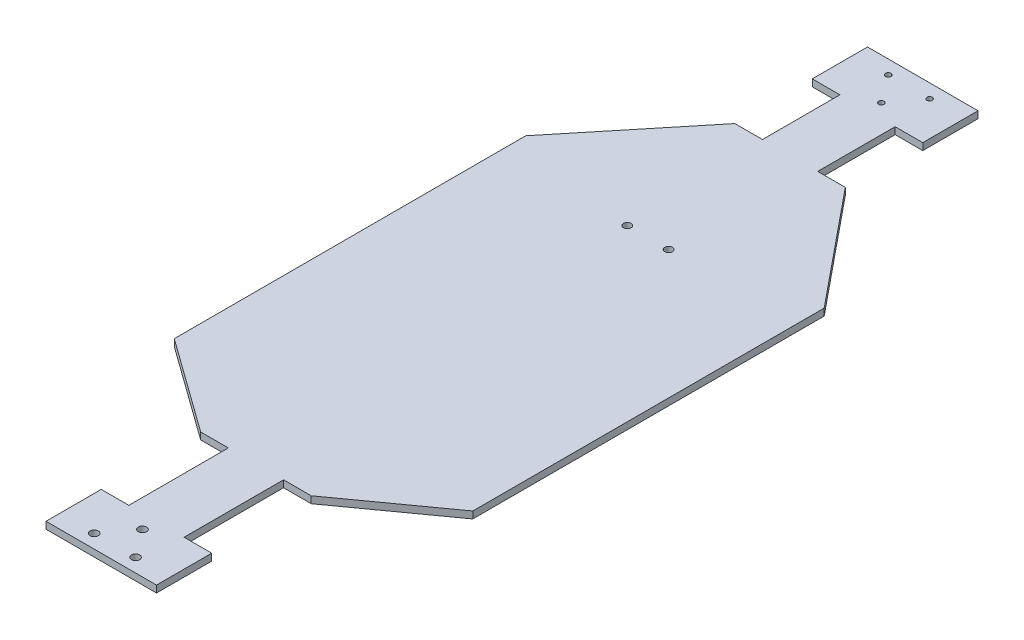
SolidWorks part; units mm, degrees
ref_plane "Front Plane" through (0, 0, 0) normal (0, 0, 1) x (1, 0, 0)
ref_plane "Top Plane" through (0, 0, 0) normal (0, 1, 0) x (1, 0, 0)
ref_plane "Right Plane" through (0, 0, 0) normal (1, 0, 0) x (0, 0, -1)
sketch "Sketch1" plane through (0, 0, 0) normal (0, 1, 0) x (1, 0, 0)
  line L0 (-12.736, 155.2654) -> (-12.736, -94.859) construction
  line L1 (-63.5899, 30.2032) -> (63.4101, 30.2032) construction
  line L2 (32.0615, 155.2654) -> (12.664, 155.2654)
  line L3 (25.3101, -48.4064) -> (63.4101, -31.575)
  line L4 (63.4101, -31.575) -> (63.4101, 91.9815)
  line L5 (-12.736, -94.859) -> (-12.7899, -144.7536)
  line L6 (-12.7899, -144.7536) -> (-25.4899, -144.7536)
  line L7 (12.664, 155.2654) -> (12.664, -94.859) construction
  line L8 (32.0615, 127.4908) -> (32.0615, 155.2654)
  line L9 (-32.2414, 155.2654) -> (-32.2414, 127.4908)
  line L10 (-32.2414, 155.2654) -> (-12.736, 155.2654)
  line L11 (12.664, 200.654) -> (12.664, 155.2654)
  line L12 (-25.4899, -48.4064) -> (-63.5899, -31.575)
  line L13 (25.6751, 200.654) -> (12.664, 200.654)
  line L14 (25.6751, 226.054) -> (25.6751, 200.654)
  line L15 (-63.5899, -31.575) -> (-63.5899, 91.9815)
  line L16 (-25.4899, -144.7536) -> (-25.4899, -170.1536)
  line L17 (-25.4899, -170.1536) -> (25.3101, -170.1536)
  line L18 (25.3101, -170.1536) -> (25.3101, -144.7536)
  line L19 (25.3101, -144.7536) -> (12.6101, -144.7536)
  line L20 (12.6101, -144.7536) -> (12.664, -94.859)
  line L21 (-25.4899, -94.859) -> (-12.736, -94.859)
  line L22 (-25.4899, -94.859) -> (-25.4899, -48.4064)
  line L23 (25.3101, -48.4064) -> (25.3101, -94.859)
  line L24 (25.3101, -94.859) -> (12.664, -94.859)
  line L25 (-25.6858, 226.054) -> (25.6751, 226.054)
  line L26 (-25.6858, 200.654) -> (-25.6858, 226.054)
  line L27 (-32.2414, 127.4908) -> (-63.5899, 91.9815)
  line L28 (-12.736, 200.654) -> (-25.6858, 200.654)
  line L29 (-12.736, 155.2654) -> (-12.736, 200.654)
  line L30 (32.0615, 127.4908) -> (63.4101, 91.9815)
  line L31 (-0.0899, 0) -> (-0.0899, 280.8086) construction
  point P14 (12.664, 30.2032)
  point P16 (-12.736, 30.2032)
  point P39 (-0.0899, 30.2032)
  dimension "D1" = 127
  dimension "D3" = 25.4
  dimension "D7" = 50.8
extrude "Boss-Extrude1" [suppressed] add sketch "Sketch1" along normal blind 3.175
sketch "Sketch2" plane through (0, 0, 0) normal (0, 1, 0) x (1, 0, 0)
  line L0 (-687.675, 0) -> (813.0168, 0) construction
  line L1 (25.4, -151.5334) -> (-25.4, -151.5334)
  line L2 (-25.4, -151.5334) -> (-25.4, -126.1334)
  line L3 (-25.4, -126.1334) -> (-12.7, -126.1334)
  line L4 (-12.7, -126.1334) -> (-12.7, -80.4134)
  line L5 (-12.7, -80.4134) -> (-25.4, -80.4134)
  line L6 (-25.4, -80.4134) -> (-68.6199, -49.3237)
  line L7 (-68.6199, -49.3237) -> (-68.6199, 0)
  line L8 (0, 239.9419) -> (0, -1315.2354) construction
  line L9 (-68.6199, 0) -> (-68.6199, 112.2518)
  line L10 (-68.6199, 112.2518) -> (-25.4, 165.1934)
  line L11 (-25.4, 165.1934) -> (-12.7, 165.1934)
  line L12 (-12.7, 165.1934) -> (-12.7, 200.7957)
  line L13 (-12.7, 200.7957) -> (-25.4, 200.7957)
  line L14 (-25.4, 200.7957) -> (-25.4, 226.1957)
  line L15 (-25.4, 226.1957) -> (25.4, 226.1957)
  line L16 (25.4, 200.7957) -> (25.4, 226.1957)
  line L17 (12.7, 200.7957) -> (25.4, 200.7957)
  line L18 (12.7, 165.1934) -> (12.7, 200.7957)
  line L19 (25.4, 165.1934) -> (12.7, 165.1934)
  line L20 (68.6199, 112.2518) -> (25.4, 165.1934)
  line L21 (68.6199, 0) -> (68.6199, 112.2518)
  line L22 (68.6199, -49.3237) -> (68.6199, 0)
  line L23 (25.4, -80.4134) -> (68.6199, -49.3237)
  line L24 (12.7, -80.4134) -> (25.4, -80.4134)
  line L25 (12.7, -126.1334) -> (12.7, -80.4134)
  line L26 (25.4, -126.1334) -> (12.7, -126.1334)
  line L27 (25.4, -151.5334) -> (25.4, -126.1334)
  line L28 (13.342, 219.8457) -> (-18.32, 219.8457) construction
  line L29 (12.7, 165.1934) -> (12.7, -80.4134) construction
  line L30 (-12.7, 165.1934) -> (-12.7, -80.4134) construction
  line L31 (12.7, 165.1934) -> (6.35, 165.1934) construction
  line L32 (-6.35, 165.1934) -> (-6.35, -80.4134) construction
  line L33 (12.7, -80.4134) -> (-12.7, -80.4134) construction
  line L34 (6.35, -80.4134) -> (6.35, 165.1934) construction
  line L35 (-6.35, 165.1934) -> (-12.7, 165.1934) construction
  line L36 (-9.525, 165.1934) -> (-9.525, -80.4134) construction
  line L37 (9.525, 165.1934) -> (9.525, -80.4134) construction
  line L38 (-127.356, 99.8299) -> (147.3122, 99.8299) construction
  circle A0 centre (-9.525, 219.8457) radius 1.2564
  circle A1 centre (9.525, 219.8457) radius 1.2564
  circle A2 centre (0, 207.1457) radius 1.2564
  circle A3 centre (9.525, -145.2793) radius 1.905 construction
  circle A4 centre (0, -132.5793) radius 1.905 construction
  circle A5 centre (-9.525, -145.2793) radius 1.905 construction
  circle A6 centre (9.525, -145.2793) radius 1.905
  circle A7 centre (0, -132.5793) radius 1.905
  circle A8 centre (-9.525, -145.2793) radius 1.905
  circle A9 centre (-9.525, 99.8299) radius 1.7762
  circle A10 centre (9.525, 99.8299) radius 1.7762
  point P21 (0, 226.1957)
  point P33 (0, -151.5334)
  dimension "D1" = 25.4
  dimension "D2" = 50.8
  dimension "D3" = 45.72
  dimension "D4" = 12.7
  dimension "D5" = 9.525
  dimension "D6" = 9.525
  dimension "D7" = 12.7
  dimension "D8" = 6.35
  dimension "D9" = 6.35
  dimension "D10" = 6.35
extrude "Boss-Extrude2" add sketch "Sketch2" along normal blind 3.175 separate body
